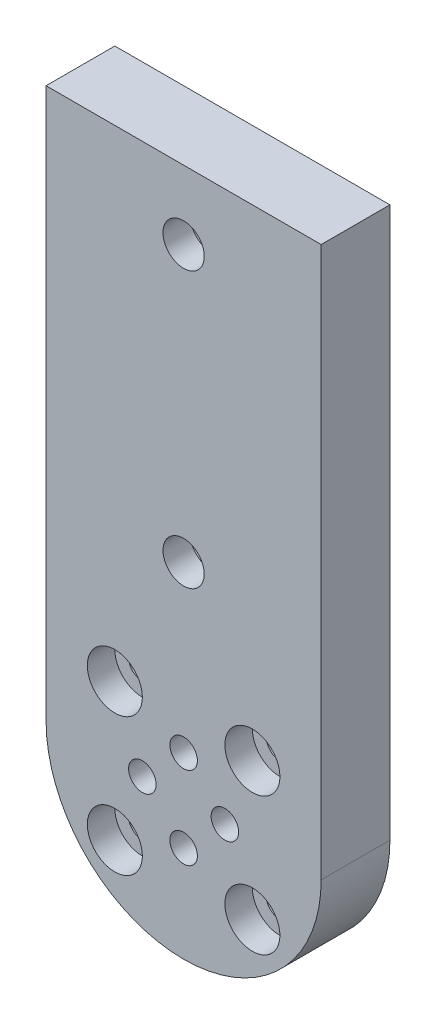
SolidWorks part; units mm, degrees
material "1060 Alloy"
ref_plane "Front Plane" through (0, 0, 0) normal (0, 0, 1) x (1, 0, 0)
ref_plane "Top Plane" through (0, 0, 0) normal (0, 1, 0) x (1, 0, 0)
ref_plane "Right Plane" through (0, 0, 0) normal (1, 0, 0) x (0, 0, -1)
sketch "Sketch2" plane through (0, 0, 0) normal (0, 0, 1) x (1, 0, 0)
  line L0 (-10, 0) -> (-10, 40)
  line L1 (-5, 5) -> (5, 5) construction
  line L2 (-5, 5) -> (-5, -5) construction
  line L3 (-5, -5) -> (5, -5) construction
  line L4 (5, 5) -> (5, -5) construction
  line L5 (-5, 5) -> (5, -5) construction
  line L6 (-5, -5) -> (5, 5) construction
  line L7 (10, 0) -> (10, 40)
  line L8 (-10, 40) -> (10, 40)
  line L9 (0, 40) -> (0, -10) construction
  circle A0 centre (0, 0) radius 10
  circle A1 centre (-5, 5) radius 1
  circle A2 centre (5, 5) radius 1
  circle A3 centre (-5, -5) radius 1
  circle A4 centre (5, -5) radius 1
  circle A5 centre (0, 35) radius 1.5
  circle A6 centre (0, 15) radius 1.5
  dimension "D4" = 2
  dimension "D5" = 2
  dimension "D6" = 2
  dimension "D7" = 2
  dimension "D9" = 3
  dimension "D10" = 3
  dimension "D13" = 20
  dimension "D2" = 10
  dimension "D3" = 10
  dimension "D8" = 40
  dimension "D11" = 20
  dimension "D12" = 5
extrude "Boss-Extrude1" add sketch "Sketch2" along normal blind 5 contours A6 A0 A4 A3 A2 A1 | A6 A0 L7 L8 L0 A5
sketch "Sketch5" plane through (0, 0, 5) normal (0, 0, 1) x (1, 0, 0)
  line L0 (-10, 0) -> (10, 0) construction
  line L1 (0, -13.5) -> (0, 13.5) construction
  circle A0 centre (-5, 5) radius 2
  circle A1 centre (5, 5) radius 2
  circle A2 centre (5, -5) radius 2
  circle A3 centre (-5, -5) radius 2
  circle A4 centre (0, 15) radius 1.5 construction
  circle A5 centre (0, 3) radius 1
  circle A6 centre (-3, 0) radius 1
  circle A7 centre (3, 0) radius 1
  circle A8 centre (0, -3) radius 1
  point P17 (0, 0)
  point P24 (0, 0)
  dimension "D1" = 4
  dimension "D2" = 4
  dimension "D3" = 4
  dimension "D4" = 4
  dimension "D5" = 2
  dimension "D10" = 2
  dimension "D11" = 2
  dimension "D12" = 2
  dimension "D6" = 3
  dimension "D7" = 3
  dimension "D8" = 3
  dimension "D9" = 3
extrude "Cut-Extrude2" cut sketch "Sketch5" against normal blind 2
sketch "Sketch6" plane through (0, 0, 0) normal (0, 0, -1) x (-1, 0, 0)
  line L0 (0, 40) -> (0, -10) construction
  circle A0 centre (0, 35) radius 3.5
  circle A1 centre (0, 15) radius 3.5
  dimension "D1" = 7
  dimension "D2" = 7
extrude "Cut-Extrude3" cut sketch "Sketch6" against normal blind 3
